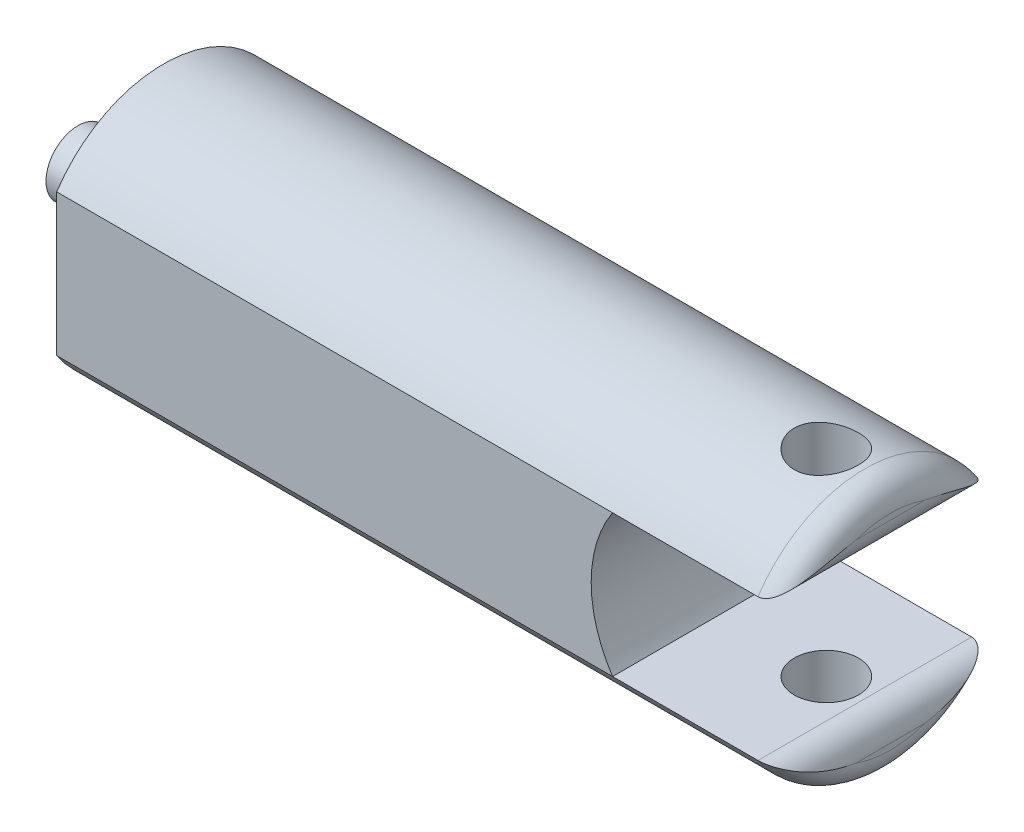
SolidWorks part; units mm, degrees
ref_plane "Front Plane" through (0, 0, 0) normal (0, 0, 1) x (1, 0, 0)
ref_plane "Top Plane" through (0, 0, 0) normal (0, 1, 0) x (1, 0, 0)
ref_plane "Right Plane" through (0, 0, 0) normal (1, 0, 0) x (0, 0, -1)
sketch "Sketch1" plane through (0, 0, 0) normal (1, 0, 0) x (0, 0, -1)
  line L0 (0, 30) -> (0, -30) construction
  line L1 (-25, 16.5831) -> (-25, -16.5831)
  line L2 (25, 16.5831) -> (25, -16.5831)
  line L3 (-25, 30) -> (-25, -30) construction
  line L4 (25, 30) -> (25, -30) construction
  arc A0 (25, 16.5831) -> (-25, 16.5831) centre (0, 0) ccw
  arc A1 (-25, -16.5831) -> (25, -16.5831) centre (0, 0) ccw
  dimension "D1" = 60
  dimension "D2" = 25
  dimension "D3" = 25
extrude "Boss-Extrude1" add sketch "Sketch1" along normal blind 170
sketch "Sketch5" plane through (0, 0, 0) normal (-1, 0, 0) x (0, 0, 1)
  circle A0 centre (0, 0) radius 7.5
  dimension "D1" = 15
extrude "Boss-Extrude2" add sketch "Sketch5" along normal blind 20
sketch "Sketch7" plane through (0, 0, -25) normal (0, 0, -1) x (-1, 0, 0)
  line L0 (-170, 16.5831) -> (0, 16.5831) construction
  line L1 (-180, -16.5831) -> (-130, -16.5831)
  line L2 (-180, -16.5831) -> (-180, 16.5831) construction
  line L3 (-180, 16.5831) -> (-130, 16.5831)
  line L4 (-130, -16.5831) -> (-130, 16.5831) construction
  line L5 (-180, -16.5831) -> (-130, 16.5831) construction
  line L6 (-180, 16.5831) -> (-130, -16.5831) construction
  line L7 (-170, -16.5831) -> (-170, 16.5831) construction
  arc A0 (-180, 16.5831) -> (-180, -16.5831) centre (-155, 0) ccw
  arc A1 (-130, -16.5831) -> (-130, 16.5831) centre (-155, 0) ccw
  point P0 (-155, 0)
  dimension "D3" = 50
  dimension "D1" = 33.1662
  dimension "D2" = 15
extrude "Cut-Extrude1" cut sketch "Sketch7" against normal through all
sketch "Sketch8" plane through (0, 0, 0) normal (0, 1, 0) x (1, 0, 0)
  line L0 (170, -25) -> (170, 25) construction
  circle A0 centre (155, 0) radius 7.5
  point P4 (170, 0)
  dimension "D1" = 15
  dimension "D2" = 15
extrude "Cut-Extrude2" cut sketch "Sketch8" against normal mid plane 97
fillet "Fillet1" radius 6 4 edges at (170, -16.5831, 0) (170, 16.5831, 0) (170, -30, 0) (170, 30, 0)
